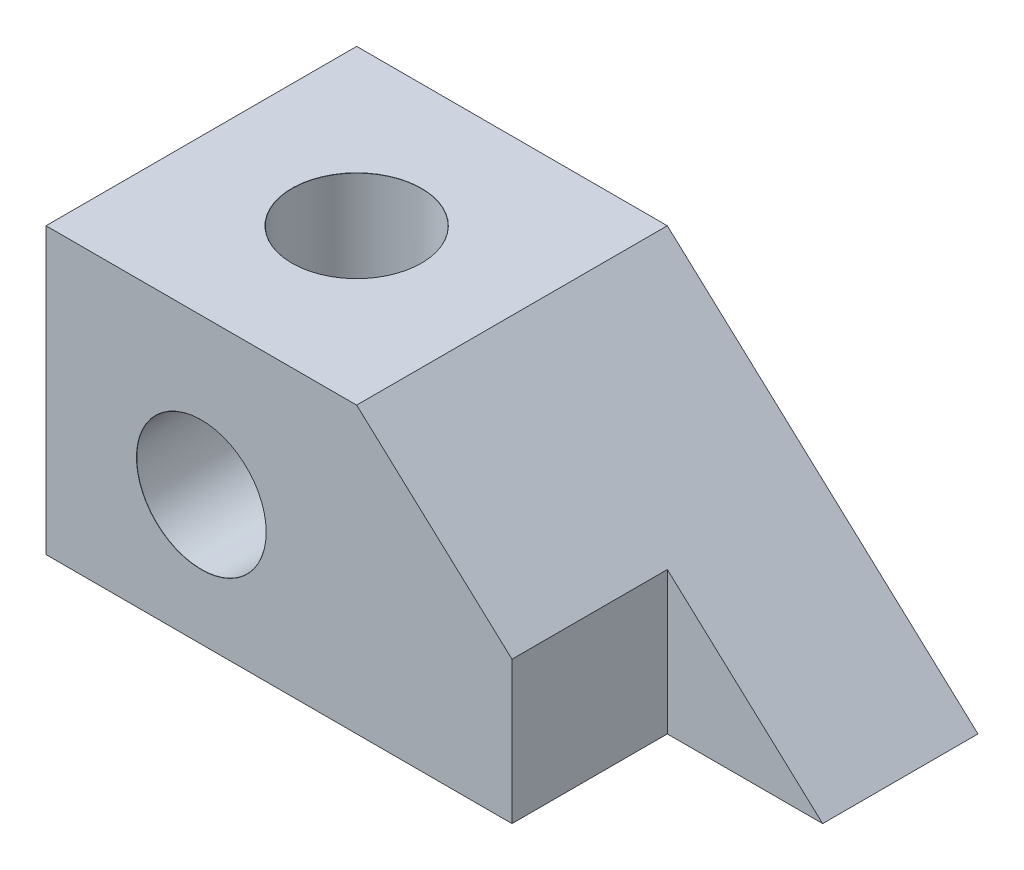
SolidWorks part; units mm, degrees
ref_plane "정면" through (0, 0, 0) normal (0, 0, 1) x (1, 0, 0)
ref_plane "윗면" through (0, 0, 0) normal (0, 1, 0) x (1, 0, 0)
ref_plane "우측면" through (0, 0, 0) normal (1, 0, 0) x (0, 0, -1)
sketch "Sketch1" plane through (0, 0, 0) normal (0, 1, 0) x (1, 0, 0)
  line L1 (0, 0) -> (90, 0)
  line L2 (0, 0) -> (0, 60)
  line L3 (0, 60) -> (102.4873, 60)
  line L4 (90, 0) -> (90, 30)
  line L5 (102.4873, 60) -> (120, 60)
  line L7 (90, 30) -> (120, 30)
  line L8 (120, 60) -> (120, 30)
  dimension "D1" = 60
  dimension "D2" = 90
  dimension "D3" = 30
  dimension "D4" = 30
extrude "Boss-Extrude1" add sketch "Sketch1" along normal blind 55
sketch "Sketch4" plane through (0, 0, 0) normal (0, 0, 1) x (1, 0, 0)
  line L0 (60, 55) -> (120, 0)
  line L1 (0, 55) -> (90, 55) construction
  line L2 (120, 0) -> (120, 55)
  line L3 (120, 55) -> (120, 0) construction
  line L4 (120, 55) -> (60, 55)
  line L5 (0, 55) -> (0, 0) construction
  dimension "D1" = 60
extrude "Cut-Extrude2" cut sketch "Sketch4" against normal through all
hole_wizard "Ø25.0 (25) Diameter Hole3" positions "3DSketch3" profile "Sketch11" hole size "Ø25.0" standard "Ansi Metric" end condition through all
sketch3d "3DSketch3"
  line L0 (0, 55, 0) -> (0, 0, 0) construction
  line L1 (0, 55, 0) -> (60, 55, 0) construction
  point P0 (30, 25, 0)
  dimension "D1" = 30
  dimension "D2" = 30
sketch "Sketch11" plane through (30, 25, 0) normal (1, 0, 0) x (0, -1, 0)
  line L0 (0, 0) -> (0, 60)
  line L1 (0, 60) -> (12.5, 60)
  line L2 (12.5, 60) -> (12.5, 0.025)
  line L3 (12.5, 0.025) -> (12.525, 0)
  line L5 (12.525, 0) -> (0, 0)
  line L6 (-12.5, 0.025) -> (-12.525, 0) construction
  line L11 (0, -6.35) -> (0, 107.95) construction
  dimension "관통 구멍 지름" = 25
  dimension "관통 구멍 깊이" = 60
  dimension "표면 카운터싱크 지름" = 25.05
  dimension "표면 카운터싱크 각도" = 90
hole_wizard "Ø25.0 (25) Diameter Hole4" positions "3DSketch4" profile "Sketch12" hole size "Ø25.0" standard "Ansi Metric" end condition through all
sketch3d "3DSketch4"
  line L0 (0, 55, -60) -> (0, 55, 0) construction
  line L1 (60, 55, -60) -> (0, 55, -60) construction
  point P0 (30, 55, -30)
  dimension "D1" = 30
  dimension "D2" = 30
sketch "Sketch12" plane through (30, 55, -30) normal (1, 0, 0) x (0, 0, 1)
  line L0 (0, 0) -> (0, 55)
  line L1 (0, 55) -> (12.5, 55)
  line L2 (12.5, 55) -> (12.5, 0.025)
  line L3 (12.5, 0.025) -> (12.525, 0)
  line L5 (12.525, 0) -> (0, 0)
  line L6 (-12.5, 0.025) -> (-12.525, 0) construction
  line L11 (0, -6.35) -> (0, 107.95) construction
  dimension "관통 구멍 지름" = 25
  dimension "관통 구멍 깊이" = 55
  dimension "표면 카운터싱크 지름" = 25.05
  dimension "표면 카운터싱크 각도" = 90
